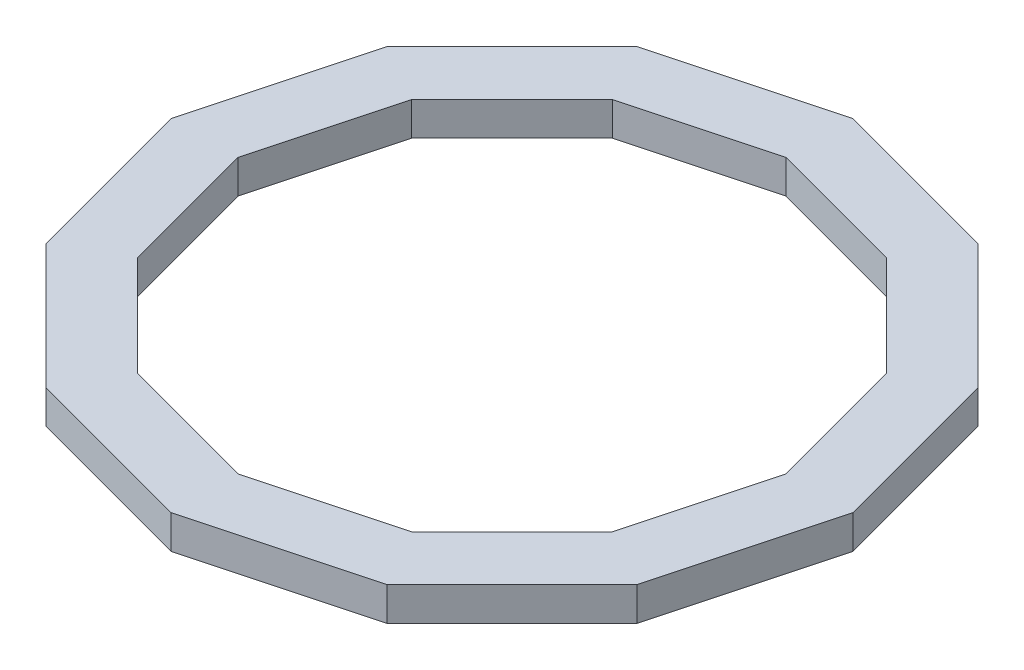
SolidWorks part; units mm, degrees
ref_plane "Front Plane" through (0, 0, 0) normal (0, 0, 1) x (1, 0, 0)
ref_plane "Top Plane" through (0, 0, 0) normal (0, 1, 0) x (1, 0, 0)
ref_plane "Right Plane" through (0, 0, 0) normal (1, 0, 0) x (0, 0, -1)
sketch "Sketch2" plane through (0, 0, 0) normal (0, 1, 0) x (1, 0, 0)
  line L0 (-193.8227, 0) -> (-155.6935, 0) construction
  line L1 (-193.8227, 0) -> (-167.8554, -96.9113)
  line L2 (-167.8554, -96.9113) -> (-96.9113, -167.8554)
  line L3 (-96.9113, -167.8554) -> (0, -193.8227)
  line L4 (0, -193.8227) -> (96.9113, -167.8554)
  line L5 (96.9113, -167.8554) -> (167.8554, -96.9113)
  line L6 (167.8554, -96.9113) -> (193.8227, 0)
  line L7 (193.8227, 0) -> (167.8554, 96.9113)
  line L8 (167.8554, 96.9113) -> (96.9113, 167.8554)
  line L9 (96.9113, 167.8554) -> (0, 193.8227)
  line L10 (0, 193.8227) -> (-96.9113, 167.8554)
  line L11 (-96.9113, 167.8554) -> (-167.8554, 96.9113)
  line L12 (-167.8554, 96.9113) -> (-193.8227, 0)
  line L13 (-155.6935, 0) -> (-134.8345, -77.8467)
  line L14 (-134.8345, -77.8467) -> (-77.8467, -134.8345)
  line L15 (-77.8467, -134.8345) -> (0, -155.6935)
  line L16 (0, -155.6935) -> (77.8467, -134.8345)
  line L17 (77.8467, -134.8345) -> (134.8345, -77.8467)
  line L18 (134.8345, -77.8467) -> (155.6935, 0)
  line L19 (155.6935, 0) -> (134.8345, 77.8467)
  line L20 (134.8345, 77.8467) -> (77.8467, 134.8345)
  line L21 (77.8467, 134.8345) -> (0, 155.6935)
  line L22 (0, 155.6935) -> (-77.8467, 134.8345)
  line L23 (-77.8467, 134.8345) -> (-134.8345, 77.8467)
  line L24 (-134.8345, 77.8467) -> (-155.6935, 0)
  line L25 (0, 0) -> (-155.6935, 0) construction
  circle A0 centre (0, 0) radius 187.2183 construction
  circle A1 centre (0, 0) radius 150.3883 construction
  dimension "D1" = 100.33
  dimension "D2" = 36.83
extrude "Boss-Extrude2" add sketch "Sketch2" along normal blind 19.05 separate body
